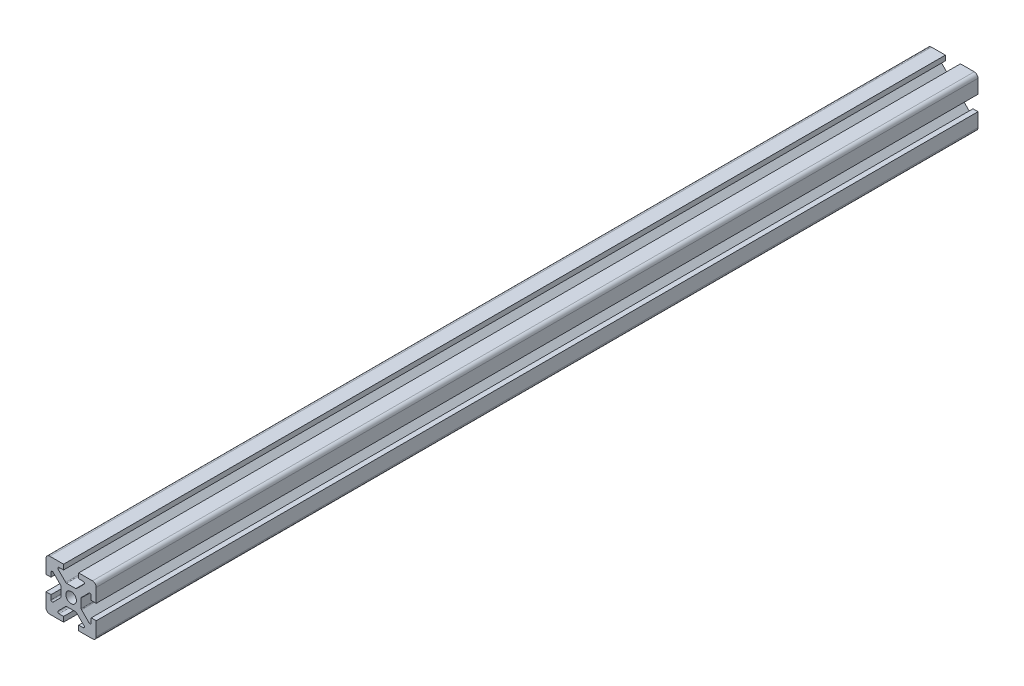
SolidWorks part; units mm, degrees
ref_plane "前基準面" through (0, 0, 0) normal (0, 0, 1) x (1, 0, 0)
ref_plane "上基準面" through (0, 0, 0) normal (0, 1, 0) x (1, 0, 0)
ref_plane "右基準面" through (0, 0, 0) normal (1, 0, 0) x (0, 0, -1)
sketch "草圖2" plane through (0, 0, 0) normal (0, 0, 1) x (1, 0, 0)
  line L0 (55, 0) -> (-55, 0) construction
  line L1 (-10, 10) -> (10, 10)
  line L2 (-10, 10) -> (-10, -10)
  line L3 (-10, -10) -> (10, -10)
  line L4 (10, 10) -> (10, -10)
  line L5 (0, -55) -> (0, 55) construction
  dimension "D1" = 20
  dimension "D2" = 20
  dimension "D3" = 10
  dimension "D4" = 10
extrude "填料-伸長1" add sketch "草圖2" along normal blind 351
fillet "圓角1" radius 1.5 4 edges at (-10, -10, 175.5) (10, -10, 175.5) (10, 10, 175.5) (-10, 10, 175.5)
sketch "草圖3" plane through (0, 0, 351) normal (0, 0, 1) x (1, 0, 0)
  line L0 (10, 3) -> (8, 3)
  line L1 (10, -8.5) -> (10, 8.5) construction
  line L2 (8, 3) -> (8, 4.7929)
  line L3 (7.1464, 5.1464) -> (4.1464, 2.1464)
  line L4 (4, 1.7929) -> (4, -1.7929)
  line L5 (4.1464, -2.1464) -> (7.1464, -5.1464)
  line L6 (8, -4.7929) -> (8, -3)
  line L7 (8, -3) -> (10, -3)
  line L8 (10, -3) -> (10, 3)
  line L9 (-8.5, -10) -> (8.5, -10) construction
  line L10 (-3, -10) -> (3, -10)
  line L11 (3, -10) -> (3, -8)
  line L12 (3, -8) -> (4.7929, -8)
  line L13 (5.1464, -7.1464) -> (2.1464, -4.1464)
  line L14 (1.7929, -4) -> (-1.7929, -4)
  line L15 (-2.1464, -4.1464) -> (-5.1464, -7.1464)
  line L16 (-4.7929, -8) -> (-3, -8)
  line L17 (-3, -8) -> (-3, -10)
  line L18 (-10, 3) -> (-10, -3)
  line L19 (-10, -3) -> (-8, -3)
  line L20 (-8, -3) -> (-8, -4.7929)
  line L21 (-7.1464, -5.1464) -> (-4.1464, -2.1464)
  line L22 (-4, -1.7929) -> (-4, 1.7929)
  line L23 (-4.1464, 2.1464) -> (-7.1464, 5.1464)
  line L24 (-8, 4.7929) -> (-8, 3)
  line L25 (-8, 3) -> (-10, 3)
  line L26 (3, 10) -> (-3, 10)
  line L27 (-3, 10) -> (-3, 8)
  line L28 (-3, 8) -> (-4.7929, 8)
  line L29 (-5.1464, 7.1464) -> (-2.1464, 4.1464)
  line L30 (-1.7929, 4) -> (1.7929, 4)
  line L31 (2.1464, 4.1464) -> (5.1464, 7.1464)
  line L32 (4.7929, 8) -> (3, 8)
  line L33 (3, 8) -> (3, 10)
  circle A0 centre (0, 0) radius 2.1
  arc A1 (7.1464, -5.1464) -> (8, -4.7929) centre (7.5, -4.7929) ccw
  arc A2 (4, -1.7929) -> (4.1464, -2.1464) centre (4.5, -1.7929) ccw
  arc A3 (4.1464, 2.1464) -> (4, 1.7929) centre (4.5, 1.7929) ccw
  arc A4 (8, 4.7929) -> (7.1464, 5.1464) centre (7.5, 4.7929) ccw
  arc A5 (4.7929, -8) -> (5.1464, -7.1464) centre (4.7929, -7.5) ccw
  arc A6 (2.1464, -4.1464) -> (1.7929, -4) centre (1.7929, -4.5) ccw
  arc A7 (-1.7929, -4) -> (-2.1464, -4.1464) centre (-1.7929, -4.5) ccw
  arc A8 (-5.1464, -7.1464) -> (-4.7929, -8) centre (-4.7929, -7.5) ccw
  arc A9 (-8, -4.7929) -> (-7.1464, -5.1464) centre (-7.5, -4.7929) ccw
  arc A10 (-4.1464, -2.1464) -> (-4, -1.7929) centre (-4.5, -1.7929) ccw
  arc A11 (-4, 1.7929) -> (-4.1464, 2.1464) centre (-4.5, 1.7929) ccw
  arc A12 (-7.1464, 5.1464) -> (-8, 4.7929) centre (-7.5, 4.7929) ccw
  arc A13 (-4.7929, 8) -> (-5.1464, 7.1464) centre (-4.7929, 7.5) ccw
  arc A14 (-2.1464, 4.1464) -> (-1.7929, 4) centre (-1.7929, 4.5) ccw
  arc A15 (1.7929, 4) -> (2.1464, 4.1464) centre (1.7929, 4.5) ccw
  arc A16 (5.1464, 7.1464) -> (4.7929, 8) centre (4.7929, 7.5) ccw
  point P17 (8, -6)
  point P24 (8, 6)
  point P76 (0, 0)
  dimension "D1" = 4.2
  dimension "D10" = 0.5
  dimension "D2" = 6
  dimension "D3" = 7
  dimension "D4" = 3
  dimension "D5" = 3
  dimension "D6" = 4
  dimension "D7" = 2
  dimension "D8" = 2
  dimension "D9" = 45
  dimension "D11" = 4
extrude "除料-伸長1" cut sketch "草圖3" against normal through all both and the other way through all
